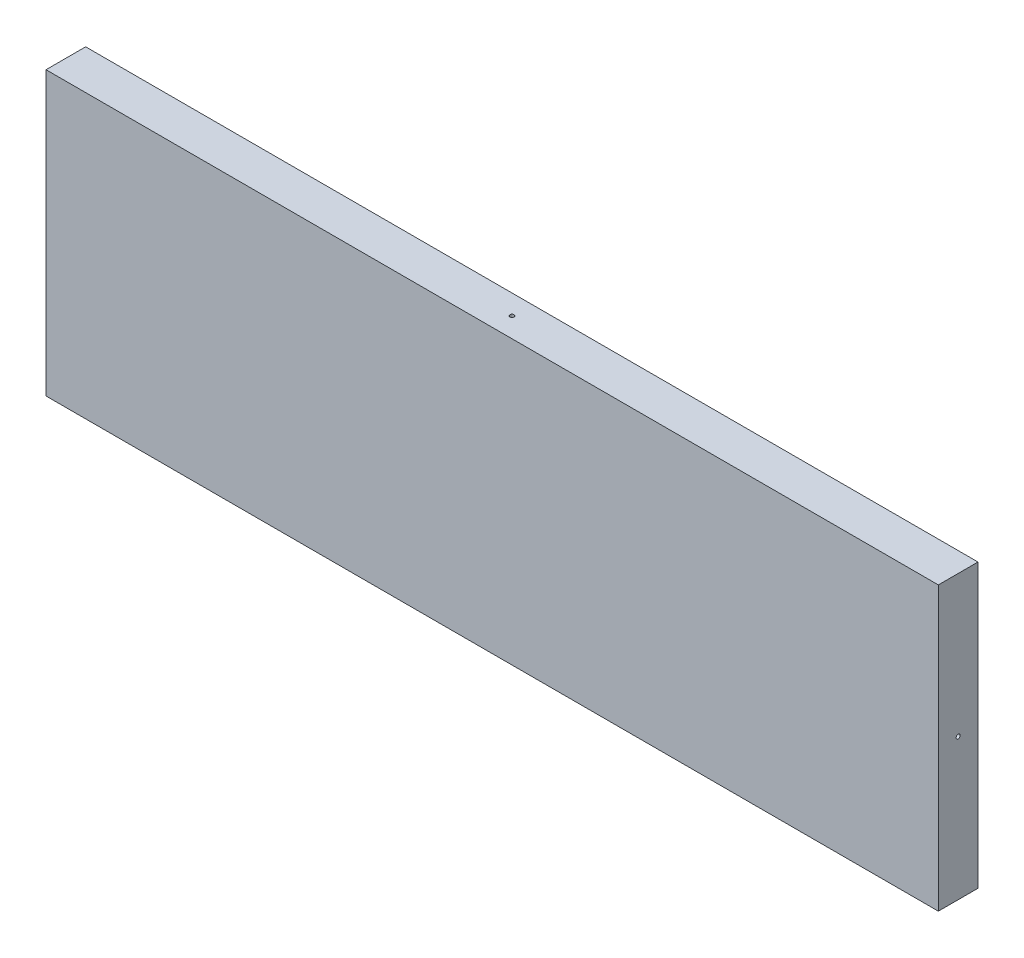
SolidWorks part; units mm, degrees
material "1.4511 (X3CrNb17)"
ref_plane "前视基准面" through (0, 0, 0) normal (0, 0, 1) x (1, 0, 0)
ref_plane "上视基准面" through (0, 0, 0) normal (0, 1, 0) x (1, 0, 0)
ref_plane "右视基准面" through (0, 0, 0) normal (1, 0, 0) x (0, 0, -1)
sketch "草图1" plane through (0, 0, 0) normal (0, 0, 1) x (1, 0, 0)
  line L1 (-450, 142.5) -> (450, 142.5)
  line L2 (-450, 142.5) -> (-450, -142.5)
  line L3 (-450, -142.5) -> (450, -142.5)
  line L4 (450, 142.5) -> (450, -142.5)
  line L5 (-450, 142.5) -> (450, -142.5) construction
  line L6 (-450, -142.5) -> (450, 142.5) construction
  point P0 (0, 0)
  dimension "D1" = 900
  dimension "D2" = 285
extrude "凸台-拉伸1" add sketch "草图1" along normal blind 40
sketch "草图2" plane through (0, 142.5, 0) normal (0, 1, 0) x (1, 0, 0)
  line L0 (-450, -40) -> (-450, 0) construction
  point P0 (0, -20)
  dimension "D1" = 450
hole_wizard "M5 螺纹孔1" positions "草图3" profile "草图4" tap size "M5" standard "GB" end condition through all
sketch "草图3" plane through (0, 142.5, 0) normal (0, 1, 0) x (1, 0, 0)
  point P0 (0, -20)
sketch "草图4" plane through (0, 142.5, 20) normal (1, 0, 0) x (0, 0, 1)
  line L0 (0, 0) -> (0, 285)
  line L1 (0, 285) -> (2.1, 285)
  line L2 (2.1, 285) -> (2.1, 0)
  line L5 (2.1, 0) -> (0, 0)
  line L11 (0, -6.35) -> (0, 107.95) construction
  dimension "通孔螺纹孔钻头直径" = 4.2
  dimension "通孔螺纹孔钻头深度" = 285
cosmetic thread "孔螺蚊线1" parameters "D2"=5
sketch "草图5" plane through (-450, 0, 0) normal (-1, 0, 0) x (0, 0, 1)
  line L0 (40, 142.5) -> (0, 142.5) construction
  point P0 (20, 0)
  dimension "D1" = 142.5
hole_wizard "M5 螺纹孔2" positions "草图6" profile "草图7" tap size "M5" standard "GB" end condition through all
sketch "草图6" plane through (-450, 0, 0) normal (-1, 0, 0) x (0, 0, 1)
  point P0 (20, 0)
sketch "草图7" plane through (-450, 0, 20) normal (0, 1, 0) x (0, 0, 1)
  line L0 (0, 0) -> (0, 900)
  line L1 (0, 900) -> (2.1, 900)
  line L2 (2.1, 900) -> (2.1, 0)
  line L5 (2.1, 0) -> (0, 0)
  line L11 (0, -6.35) -> (0, 107.95) construction
  dimension "通孔螺纹孔钻头直径" = 4.2
  dimension "通孔螺纹孔钻头深度" = 900
cosmetic thread "孔螺蚊线2" parameters "D2"=5
